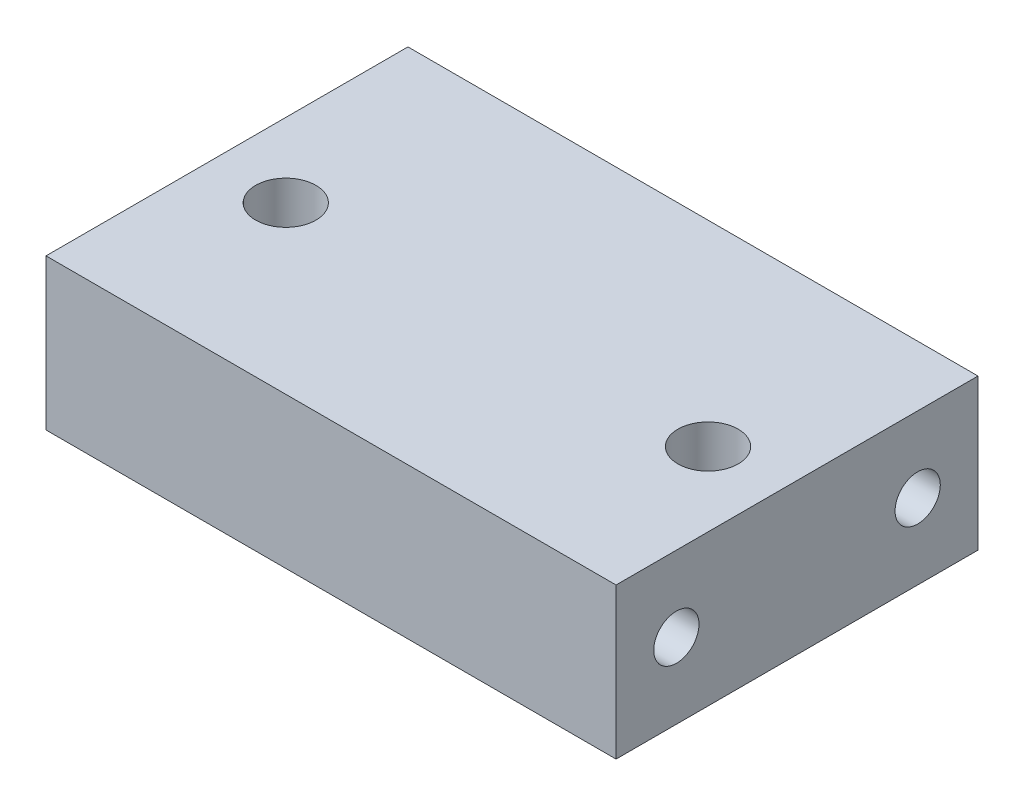
SolidWorks part; units mm, degrees
material "尼龙 101"
ref_plane "前视基准面" through (0, 0, 0) normal (0, 0, 1) x (1, 0, 0)
ref_plane "上视基准面" through (0, 0, 0) normal (0, 1, 0) x (1, 0, 0)
ref_plane "右视基准面" through (0, 0, 0) normal (1, 0, 0) x (0, 0, -1)
sketch "草图1" plane through (0, 0, 0) normal (0, 1, 0) x (1, 0, 0)
  line L1 (-18.9, -12) -> (18.9, -12)
  line L2 (-18.9, -12) -> (-18.9, 12)
  line L3 (-18.9, 12) -> (18.9, 12)
  line L4 (18.9, -12) -> (18.9, 12)
  line L5 (-18.9, -12) -> (18.9, 12) construction
  line L6 (-18.9, 12) -> (18.9, -12) construction
  point P0 (0, 0)
  dimension "D1" = 24
  dimension "D2" = 37.8
extrude "凸台-拉伸1" add sketch "草图1" along normal blind 10
sketch "草图2" plane through (0, 0, 0) normal (0, -1, 0) x (1, 0, 0)
  line L1 (-21.9, -12) -> (21.9, -12)
  line L2 (-21.9, -12) -> (-21.9, 38)
  line L3 (-21.9, 38) -> (21.9, 38)
  line L4 (21.9, -12) -> (21.9, 38)
  line L5 (-21.9, -12) -> (21.9, 38) construction
  line L6 (-21.9, 38) -> (21.9, -12) construction
  line L7 (18.9, 12) -> (18.9, -12) construction
  line L11 (18.9, -12) -> (-18.9, -12) construction
  line L12 (-18.9, 12) -> (18.9, 12) construction
  point P0 (0, 13)
  dimension "D1" = 3
  dimension "D2" = 26
extrude "凸台-拉伸2" [suppressed] add sketch "草图2" along normal blind 1.5 separate body
hole_wizard "M4 螺纹孔1" positions "草图4" profile "草图5" tap size "M4" standard "GB"
sketch "草图4" plane through (0, 10, 0) normal (0, -1, 0) x (-1, 0, 0)
  line L0 (0, 0) -> (0, 22.9057) construction
  line L4 (-18.9, 12) -> (18.9, 12) construction
  point P0 (14, -1)
  point P2 (-14, -1)
  dimension "D1" = 28
  dimension "D2" = 13
sketch "草图5" plane through (-14, 10, 1) normal (1, 0, 0) x (0, 0, 1)
  line L0 (0, 0) -> (0, 8.4914)
  line L1 (0, 8.4914) -> (1.65, 7.5)
  line L2 (1.65, 7.5) -> (1.65, 8)
  line L3 (1.65, 8) -> (2, 8)
  line L4 (2, 8) -> (2, 0)
  line L5 (2, 0) -> (0, 0)
  line L10 (0, 8.4914) -> (-1.65, 7.5) construction
  line L11 (0, -6.35) -> (0, 107.95) construction
  dimension "螺纹孔钻头直径" = 3.3
  dimension "螺纹孔钻头深度" = 7.5
  dimension "螺纹主直径" = 4
  dimension "螺纹深度" = 8
  dimension "导头角度" = 118
hole_wizard "M3 螺纹孔1" positions "草图7" profile "草图6" tap size "M3" standard "GB"
sketch "草图7" plane through (18.9, 0, 0) normal (1, 0, 0) x (0, 0, -1)
  line L4 (-12, 10) -> (-12, 0) construction
  line L6 (0, 0) -> (0, 20.2845) construction
  line L7 (-12, 10) -> (12, 10) construction
  point P0 (-8, 5)
  point P2 (8, 5)
  dimension "D1" = 5
  dimension "D3" = 4
sketch "草图6" plane through (18.9, 5, 8) normal (0, 1, 0) x (0, 0, -1)
  line L0 (0, 0) -> (0, 12.7511)
  line L1 (0, 12.7511) -> (1.25, 12)
  line L2 (1.25, 12) -> (1.25, 11.5)
  line L3 (1.25, 11.5) -> (1.5, 11.5)
  line L4 (1.5, 11.5) -> (1.5, 0)
  line L5 (1.5, 0) -> (0, 0)
  line L10 (0, 12.7511) -> (-1.25, 12) construction
  line L11 (0, -6.35) -> (0, 107.95) construction
  dimension "螺纹孔钻头直径" = 2.5
  dimension "螺纹孔钻头深度" = 12
  dimension "螺纹主直径" = 3
  dimension "螺纹深度" = 11.5
  dimension "导头角度" = 118
mirror "镜向1" about plane through (0, 0, 0) normal (1, 0, 0) of "M3 螺纹孔1"
